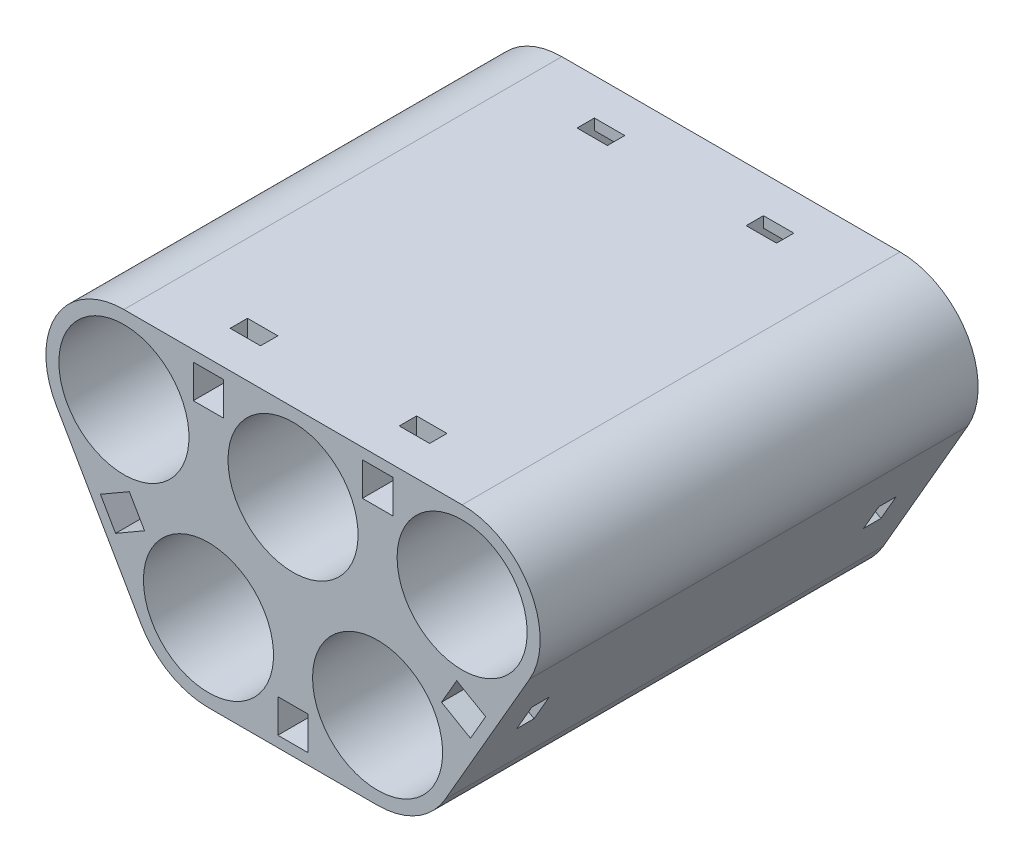
SolidWorks part; units mm, degrees
ref_plane "Front Plane" through (0, 0, 0) normal (0, 0, 1) x (1, 0, 0)
ref_plane "Top Plane" through (0, 0, 0) normal (0, 1, 0) x (1, 0, 0)
ref_plane "Right Plane" through (0, 0, 0) normal (1, 0, 0) x (0, 0, -1)
sketch "Sketch1" plane through (0, 0, 0) normal (0, 0, 1) x (1, 0, 0)
  line L0 (0, 9) -> (39, 9) construction
  line L1 (1.9558, -21.3875) -> (-7.7942, -4.5) construction
  line L2 (29.25, -25.8875) -> (9.75, -25.8875) construction
  line L3 (46.7942, -4.5) -> (37.0442, -21.3875) construction
  line L4 (0, 9) -> (39, 9)
  line L5 (1.9558, -21.3875) -> (-7.7942, -4.5)
  line L6 (29.25, -25.8875) -> (9.75, -25.8875)
  line L7 (46.7942, -4.5) -> (37.0442, -21.3875)
  arc A0 (46.7942, -4.5) -> (39, 9) centre (39, 0) ccw construction
  arc A1 (0, 9) -> (-7.7942, -4.5) centre (0, 0) ccw construction
  arc A2 (1.9558, -21.3875) -> (9.75, -25.8875) centre (9.75, -16.8875) ccw construction
  arc A3 (29.25, -25.8875) -> (37.0442, -21.3875) centre (29.25, -16.8875) ccw construction
  arc A4 (46.7942, -4.5) -> (39, 9) centre (39, 0) ccw
  arc A5 (0, 9) -> (-7.7942, -4.5) centre (0, 0) ccw
  arc A6 (1.9558, -21.3875) -> (9.75, -25.8875) centre (9.75, -16.8875) ccw
  arc A7 (29.25, -25.8875) -> (37.0442, -21.3875) centre (29.25, -16.8875) ccw
  circle A8 centre (0, 0) radius 7.5 construction
  circle A9 centre (9.75, -16.8875) radius 7.5 construction
  circle A10 centre (19.5, 0) radius 7.5 construction
  circle A11 centre (39, 0) radius 7.5 construction
  circle A12 centre (29.25, -16.8875) radius 7.5 construction
  circle A13 centre (0, 0) radius 7.5
  circle A14 centre (9.75, -16.8875) radius 7.5
  circle A15 centre (19.5, 0) radius 7.5
  circle A16 centre (39, 0) radius 7.5
  circle A17 centre (29.25, -16.8875) radius 7.5
extrude "Boss-Extrude1" add sketch "Sketch1" along normal up to surface (50.5 mm away)
sketch "Sketch2" plane through (37.0442, -21.3875, 0) normal (0.866, -0.5, 0) x (0, 0, -1)
  line L0 (0, 0) -> (0, 19.5) construction
  line L1 (0, 0) -> (0, 19.5)
  line L2 (-4.25, 8) -> (-6.25, 8)
  line L3 (-4.5, 11.25) -> (-6, 11.25)
  line L4 (-4.5, 11.25) -> (-4.5, 8.25)
  line L5 (-4.5, 8.25) -> (-6, 8.25)
  line L6 (-6, 11.25) -> (-6, 8.25)
  line L7 (-6.25, 11.5) -> (-6.25, 8)
  line L8 (-4.25, 11.5) -> (-6.25, 11.5)
  line L9 (-4.25, 11.5) -> (-4.25, 8)
  point P7 (0, 0)
  dimension "D1" = 1.5
  dimension "D2" = 0.25
extrude "Cut-Extrude1" cut sketch "Sketch2" against normal blind 1.5 contours L9 L2 L7 L8
sketch "Sketch3" plane through (0, 9, 0) normal (0, 1, 0) x (1, 0, 0)
  line L0 (31, -4.25) -> (31, -6.25)
  line L1 (30.75, -4.5) -> (27.75, -4.5)
  line L2 (30.75, -4.5) -> (30.75, -6)
  line L3 (30.75, -6) -> (27.75, -6)
  line L4 (27.75, -4.5) -> (27.75, -6)
  line L5 (31, -6.25) -> (27.5, -6.25)
  line L6 (27.5, -4.25) -> (27.5, -6.25)
  line L7 (31, -4.25) -> (27.5, -4.25)
  point P5 (0, 0)
  dimension "D1" = 1.5
  dimension "D2" = 0.25
extrude "Cut-Extrude2" cut sketch "Sketch3" against normal blind 1.5 contours L7 L6 L5 L0
sketch "Sketch4" plane through (0, -25.8875, 0) normal (0, -1, 0) x (1, 0, 0)
  line L8 (21.25, 4.25) -> (21.25, 6.25)
  line L9 (21.25, 6.25) -> (17.75, 6.25)
  line L10 (17.75, 6.25) -> (17.75, 4.25)
  line L11 (17.75, 4.25) -> (21.25, 4.25)
  line L12 (21.25, 4.25) -> (21.25, 6.25)
  line L13 (21.25, 6.25) -> (17.75, 6.25)
  line L14 (17.75, 6.25) -> (17.75, 4.25)
  line L15 (17.75, 4.25) -> (21.25, 4.25)
  dimension "D1" = 0.25
extrude "Cut-Extrude3" cut sketch "Sketch4" against normal blind 1.5
sketch "Sketch5" plane through (0, 0, 0) normal (0, 0, -1) x (-1, 0, 0)
  line L0 (-41.3702, -10.8947) -> (-39.8702, -13.4928)
  line L1 (-41.3702, -10.8947) -> (-38.4655, -9.2177)
  line L2 (-39.8702, -13.4928) -> (-36.9655, -11.8157)
  line L3 (-38.4655, -9.2177) -> (-36.9655, -11.8157)
  line L4 (-41.7117, -10.8032) -> (-39.9617, -13.8343)
  line L5 (-39.9617, -13.8343) -> (-36.6239, -11.9072)
  line L6 (-38.3739, -8.8762) -> (-36.6239, -11.9072)
  line L7 (-41.7117, -10.8032) -> (-38.3739, -8.8762)
  line L8 (-30.75, 7.5) -> (-27.75, 7.5) construction
  line L9 (-21, -24.3875) -> (-18, -24.3875) construction
  line L10 (-31, 7.75) -> (-27.5, 7.75)
  line L11 (-31, 7.75) -> (-31, 3.8959)
  line L12 (-31, 3.8959) -> (-27.5, 3.8959)
  line L13 (-27.5, 7.75) -> (-27.5, 3.8959)
  line L14 (-31, 7.75) -> (-27.5, 3.8959) construction
  line L15 (-31, 3.8959) -> (-27.5, 7.75) construction
  line L17 (-21.25, -20.7834) -> (-17.75, -20.7834)
  line L18 (-21.25, -20.7834) -> (-21.25, -24.6375)
  line L19 (-21.25, -24.6375) -> (-17.75, -24.6375)
  line L20 (-17.75, -20.7834) -> (-17.75, -24.6375)
  line L21 (-21.25, -20.7834) -> (-17.75, -24.6375) construction
  line L22 (-21.25, -24.6375) -> (-17.75, -20.7834) construction
  point P14 (-29.25, 5.8229)
  point P20 (-29.25, 7.5)
  point P24 (-19.5, -22.7104)
  point P29 (0, 0)
  point P30 (-19.5, -24.3875)
  dimension "D1" = 3.3541
  dimension "D3" = 0.25
  dimension "D4" = 0.25
  dimension "D2" = 0.25
extrude "Cut-Extrude4" cut sketch "Sketch5" against normal blind 6.25 contours L13 L10 L11 L12 | L20 L17 L18 L19 | L6 L5 L4 L7
ref_plane "Plane1" through (19.5, 0, 0) normal (1, 0, 0) x (0, 0, -1)
mirror "Mirror2" about plane through (19.5, 0, 0) normal (1, 0, 0) of "Cut-Extrude4", "Cut-Extrude3", "Cut-Extrude2", "Cut-Extrude1"
ref_plane "Plane2" through (0, 0, 25.25) normal (0, 0, -1) x (-1, 0, 0)
mirror "Mirror3" about plane through (0, 0, 25.25) normal (0, 0, -1) of "Mirror2", "Cut-Extrude4", "Cut-Extrude3", "Cut-Extrude2", "Cut-Extrude1"
equation "\"D1@Sketch5\"=sqr( 5)*1.5"
equation "\"D1@Cut-Extrude4\"=6.00mm+.25"
